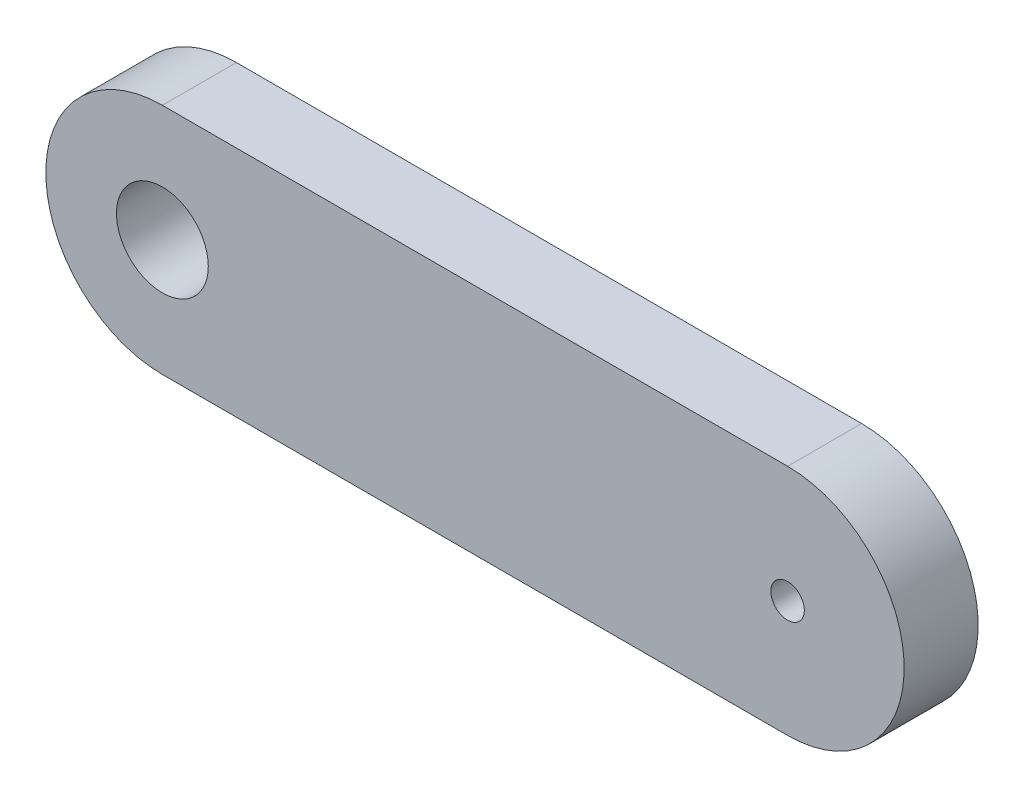
SolidWorks part; units mm, degrees
material "Balsa"
ref_plane "Front Plane" through (0, 0, 0) normal (0, 0, 1) x (1, 0, 0)
ref_plane "Top Plane" through (0, 0, 0) normal (0, 1, 0) x (1, 0, 0)
ref_plane "Right Plane" through (0, 0, 0) normal (1, 0, 0) x (0, 0, -1)
sketch "Sketch1" plane through (0, 0, 0) normal (0, 0, 1) x (1, 0, 0)
  line L0 (-26.8173, 0) -> (26.8173, 0) construction
  line L1 (-26.8173, 10) -> (26.8173, 10)
  line L2 (-26.8173, -10) -> (26.8173, -10)
  arc A0 (-26.8173, 10) -> (-26.8173, -10) centre (-26.8173, 0) ccw
  arc A1 (26.8173, -10) -> (26.8173, 10) centre (26.8173, 0) ccw
  circle A2 centre (-26.8173, 0) radius 3.9375
  circle A3 centre (26.8173, 0) radius 1.4375
  point P2 (0, 0)
  dimension "D3" = 7.875
  dimension "D4" = 2.875
  dimension "D1" = 20
  dimension "D2" = 53.6346
extrude "Boss-Extrude1" add sketch "Sketch1" along normal blind 6.35
